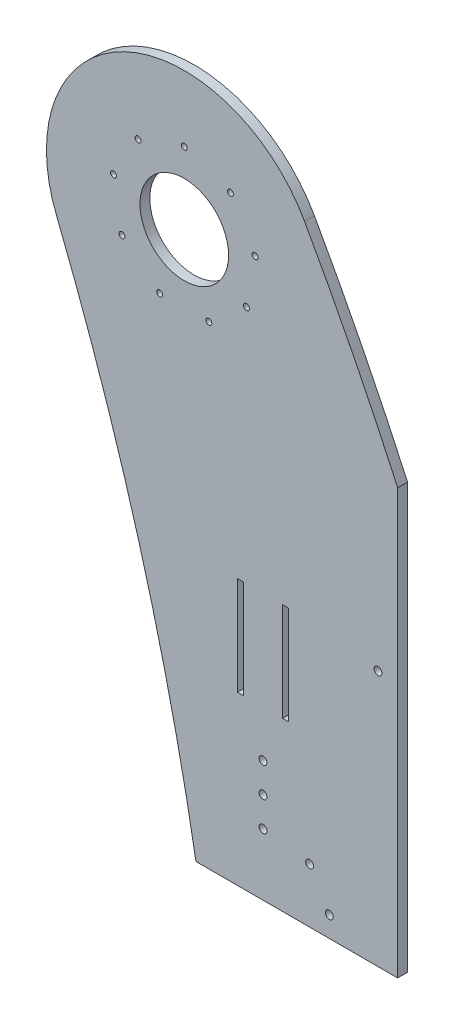
SolidWorks part; units mm, degrees
ref_plane "前视基准面" through (0, 0, 0) normal (0, 0, 1) x (1, 0, 0)
ref_plane "上视基准面" through (0, 0, 0) normal (0, 1, 0) x (1, 0, 0)
ref_plane "右视基准面" through (0, 0, 0) normal (1, 0, 0) x (0, 0, -1)
sketch "草图1" plane through (0, 0, 0) normal (0, 0, 1) x (1, 0, 0)
  line L0 (0, 0) -> (-100, 0) construction
  line L1 (0, 0) -> (100, 0) construction
  line L2 (-100, 0) -> (-100, -10)
  line L3 (-100, -10) -> (100, -10)
  line L4 (100, -10) -> (100, 0)
  line L5 (-91, -10) -> (-91, 11)
  line L6 (-91, 11) -> (-69, 11)
  line L7 (-69, 11) -> (-69, -10)
  line L9 (-93, 460) -> (-90, 460)
  line L10 (-93, 460) -> (-93, 410)
  line L11 (-93, 410) -> (-90, 410)
  line L12 (-90, 460) -> (-90, 410)
  line L13 (-93, 460) -> (-90, 410) construction
  line L14 (-93, 410) -> (-90, 460) construction
  line L15 (-70, 460) -> (-67, 460)
  line L16 (-70, 460) -> (-70, 410)
  line L17 (-70, 410) -> (-67, 410)
  line L18 (-67, 460) -> (-67, 410)
  line L19 (-70, 460) -> (-67, 410) construction
  line L20 (-70, 410) -> (-67, 460) construction
  circle A0 centre (0, 0) radius 2
  circle A1 centre (-120, 600) radius 22.5
  circle A2 centre (-120, 600) radius 70
  arc A3 (100, 0) -> (-58.9118, 634.1794) centre (-1149.7728, 23.8333) ccw
  arc A4 (-100, 0) -> (-184.9752, 573.9573) centre (-1345.2465, 108.9084) ccw
  circle A5 centre (50, 0) radius 2
  circle A6 centre (-50, 0) radius 2
  point P22 (-91.5, 435)
  point P27 (-68.5, 435)
  dimension "D1" = 4
  dimension "D2" = 45
  dimension "D4" = 120
  dimension "D5" = 140
  dimension "D8" = 2500
  dimension "D9" = 2500
  dimension "D11" = 4
  dimension "D12" = 4
  dimension "D22" = 1
  dimension "D3" = 600
  dimension "D6" = 100
  dimension "D7" = 100
  dimension "D10" = 10
  dimension "D13" = 21
  dimension "D14" = 22
  dimension "D15" = 19
  dimension "D16" = 50
  dimension "D17" = 3
  dimension "D18" = 50
  dimension "D19" = 3
  dimension "D20" = 470
  dimension "D21" = 20
extrude "凸台-拉伸1" add sketch "草图1" along normal blind 5
sketch "草图2" plane through (0, 0, 0) normal (0, 0, -1) x (-1, 0, 0)
  circle A0 centre (80, 386.4102) radius 2 construction
  circle A1 centre (80, 371.4102) radius 2 construction
  circle A2 centre (80, 356.4102) radius 2 construction
  circle A3 centre (56.3397, 352.7499) radius 2 construction
  circle A4 centre (46.3397, 335.4294) radius 2 construction
  circle A5 centre (26.3397, 300.7884) radius 2 construction
  circle A6 centre (6.3397, 266.1474) radius 2 construction
  circle A7 centre (-13.6603, 231.5064) radius 2 construction
  circle A8 centre (80, 76.4102) radius 2 construction
  circle A9 centre (80, 116.4102) radius 2 construction
  circle A10 centre (80, 236.4102) radius 2 construction
  circle A11 centre (80, 276.4102) radius 2 construction
  circle A12 centre (80, 316.4102) radius 2 construction
  circle A13 centre (80, 386.4102) radius 2
  circle A14 centre (80, 371.4102) radius 2
  circle A15 centre (80, 356.4102) radius 2
  circle A16 centre (56.3397, 352.7499) radius 2
  circle A17 centre (46.3397, 335.4294) radius 2
  circle A18 centre (26.3397, 300.7884) radius 2
  circle A19 centre (6.3397, 266.1474) radius 2
  circle A20 centre (-13.6603, 231.5064) radius 2
  circle A21 centre (80, 76.4102) radius 2
  circle A22 centre (80, 116.4102) radius 2
  circle A23 centre (80, 236.4102) radius 2
  circle A24 centre (80, 276.4102) radius 2
  circle A25 centre (80, 316.4102) radius 2
extrude "切除-拉伸1" cut sketch "草图2" against normal through all
sketch "草图3" plane through (0, 0, 5) normal (0, 0, 1) x (1, 0, 0)
  line L0 (-120, 600) -> (-120, 636.5) construction
  circle A0 centre (-120, 636.5) radius 1.5
  circle A1 centre (-96.5383, 627.9606) radius 1.5
  circle A2 centre (-84.0545, 606.3382) radius 1.5
  circle A3 centre (-88.3901, 581.75) radius 1.5
  circle A4 centre (-107.5163, 565.7012) radius 1.5
  circle A5 centre (-132.4837, 565.7012) radius 1.5
  circle A6 centre (-151.6099, 581.75) radius 1.5
  circle A7 centre (-155.9455, 606.3382) radius 1.5
  circle A8 centre (-143.4617, 627.9606) radius 1.5
  point P23 (-120, 600)
  dimension "D2" = 3
  dimension "D1" = 36.5
  dimension "D3" = 9
extrude "切除-拉伸2" cut sketch "草图3" against normal through all
ref_plane "基准面1" through (0, 325, 0) normal (0, -1, 0) x (-1, 0, 0)
split "分割1" trim tools "基准面1" bodies to split 103 resulting bodies 104 105
delete or keep bodies "实体-删除/保留 2" type delete bodies bodies 104
sketch "草图4" plane through (0, 0, 5) normal (0, 0, 1) x (1, 0, 0)
  line L0 (-11.5957, 325) -> (-11.5957, 540.605)
  line L1 (-114.0664, 325) -> (63.4043, 325) construction
  line L2 (-114.0664, 325) -> (63.4043, 325)
  line L3 (-11.5957, 325) -> (63.4043, 325)
  circle A0 centre (-21.5957, 455) radius 2
  arc A3 (-114.0664, 325) -> (-184.9752, 573.9573) centre (-1345.2465, 108.9084) ccw
  arc A4 (63.4043, 325) -> (-58.9118, 634.1794) centre (-1149.7728, 23.8333) ccw
  arc A5 (-58.9118, 634.1794) -> (-184.9752, 573.9573) centre (-120, 600) ccw
  arc A7 (63.4043, 325) -> (-11.5957, 540.605) centre (-1149.7728, 23.8333) ccw
  dimension "D3" = 4
  dimension "D4" = 130
  dimension "D5" = 10
  dimension "D1" = 75
  dimension "D2" = 0
extrude "切除-拉伸3" cut sketch "草图4" against normal blind 10
